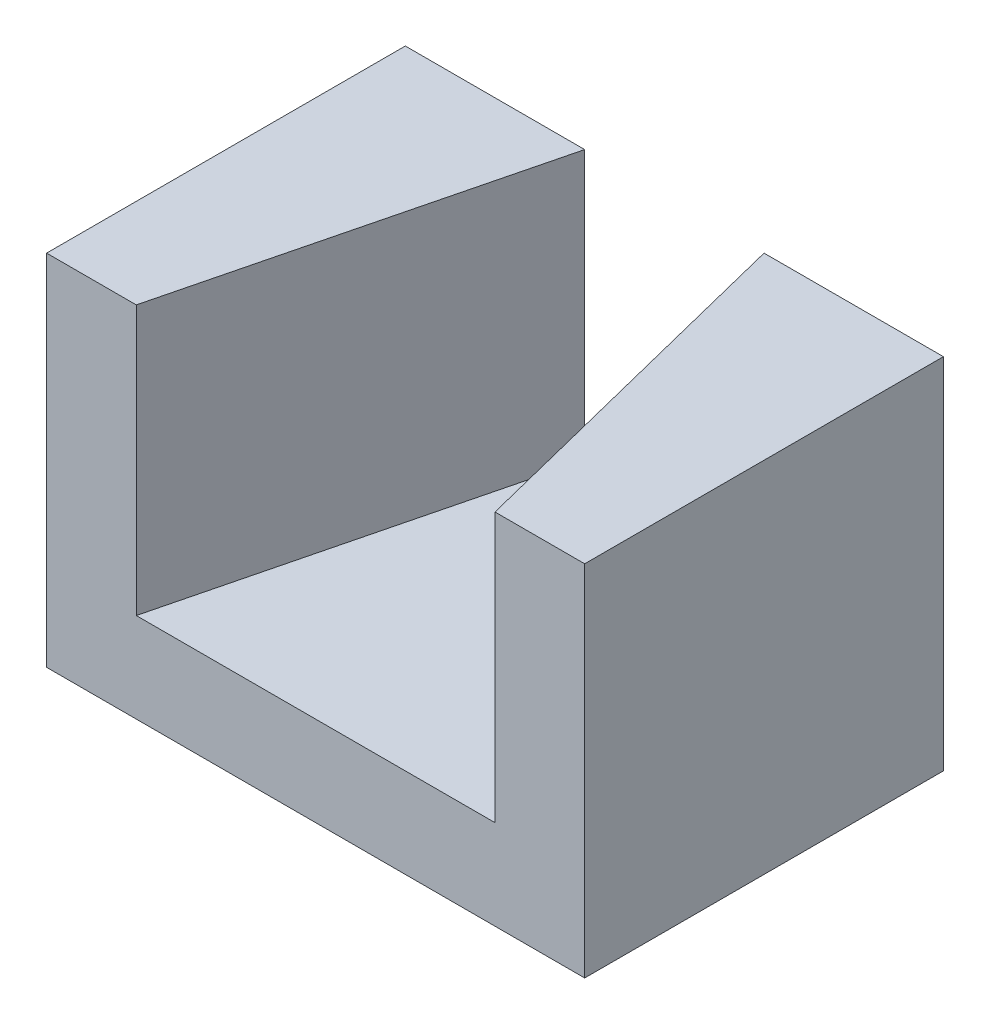
SolidWorks part; units mm, degrees
ref_plane "Front Plane" through (0, 0, 0) normal (0, 0, 1) x (1, 0, 0)
ref_plane "Top Plane" through (0, 0, 0) normal (0, 1, 0) x (1, 0, 0)
ref_plane "Right Plane" through (0, 0, 0) normal (1, 0, 0) x (0, 0, -1)
sketch "Sketch1" plane through (0, 0, 0) normal (0, 1, 0) x (1, 0, 0)
  line L1 (-30, 20) -> (30, 20)
  line L2 (-30, 20) -> (-30, -20)
  line L3 (-30, -20) -> (30, -20)
  line L4 (30, 20) -> (30, -20)
  line L5 (-30, 20) -> (30, -20) construction
  line L6 (-30, -20) -> (30, 20) construction
  point P0 (0, 0)
  dimension "D1" = 40
  dimension "D2" = 60
extrude "Boss-Extrude1" add sketch "Sketch1" along normal blind 40
sketch "Sketch2" plane through (0, 40, 0) normal (0, 1, 0) x (1, 0, 0)
  line L0 (0, 0) -> (0, 21.9225) construction
  line L1 (-10, 20) -> (10, 20)
  line L2 (30, 20) -> (-30, 20) construction
  line L3 (-20, -20) -> (20, -20)
  line L4 (-30, -20) -> (30, -20) construction
  line L5 (-10, 20) -> (-20, -20)
  line L6 (10, 20) -> (20, -20)
  point P8 (0, 20)
  point P13 (0, -20)
  dimension "D1" = 20
  dimension "D2" = 40
extrude "Cut-Extrude1" cut sketch "Sketch2" against normal blind 30
